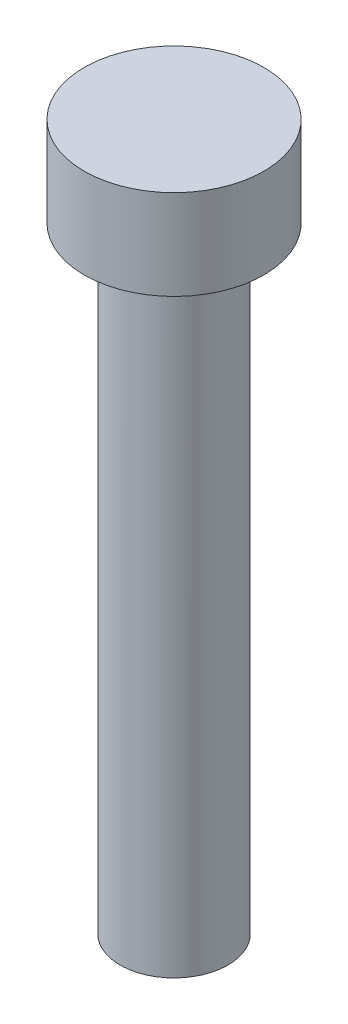
SolidWorks part; units mm, degrees
ref_plane "Front Plane" through (0, 0, 0) normal (0, 0, 1) x (1, 0, 0)
ref_plane "Top Plane" through (0, 0, 0) normal (0, 1, 0) x (1, 0, 0)
ref_plane "Right Plane" through (0, 0, 0) normal (1, 0, 0) x (0, 0, -1)
sketch "Sketch2" plane through (0, 0, 0) normal (0, 1, 0) x (1, 0, 0)
  circle A0 centre (0, 0) radius 3.048
extrude "Boss-Extrude1" add sketch "Sketch2" along normal blind 29.718
sketch "Sketch3" plane through (0, 29.718, 0) normal (0, 1, 0) x (1, 0, 0)
  circle A0 centre (0, 0) radius 5.08
extrude "Boss-Extrude2" add sketch "Sketch3" along normal blind 5.08
sketch "Sketch4" plane through (0, 0, 0) normal (0, -1, 0) x (1, 0, 0)
  circle A0 centre (0, 0) radius 3.048
extrude "Boss-Extrude3" add sketch "Sketch4" along normal blind 5.08
